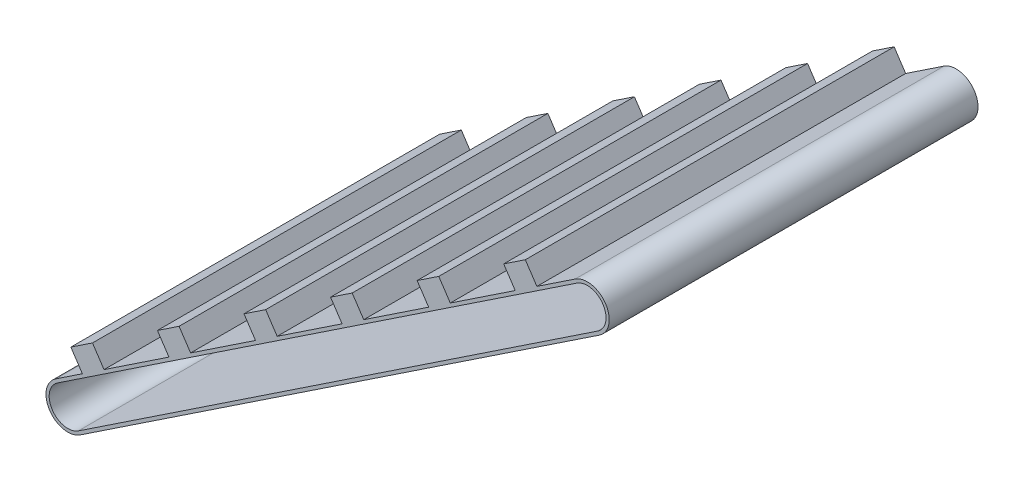
SolidWorks part; units mm, degrees
ref_plane "Front Plane" through (0, 0, 0) normal (0, 0, 1) x (1, 0, 0)
ref_plane "Top Plane" through (0, 0, 0) normal (0, 1, 0) x (1, 0, 0)
ref_plane "Right Plane" through (0, 0, 0) normal (1, 0, 0) x (0, 0, -1)
sketch "Sketch1" plane through (0, 0, 0) normal (0, 0, 1) x (1, 0, 0)
  line L0 (-1.9965, 2.9957) -> (97.8587, 69.546)
  line L1 (0, 0) -> (99.8552, 66.5503) construction
  line L2 (1.9965, -2.9957) -> (101.8517, 63.5547)
  line L3 (-2.335, 3.5035) -> (97.5202, 70.0538)
  line L4 (2.335, -3.5035) -> (102.1901, 63.0468)
  arc A0 (-1.9965, 2.9957) -> (1.9965, -2.9957) centre (0, 0) ccw
  arc A1 (101.8517, 63.5547) -> (97.8587, 69.546) centre (99.8552, 66.5503) ccw
  arc A2 (-2.335, 3.5035) -> (2.335, -3.5035) centre (0, 0) ccw
  arc A3 (102.1901, 63.0468) -> (97.5202, 70.0538) centre (99.8552, 66.5503) ccw
  dimension "D1" = 7.2
  dimension "D3" = 8.4206
  dimension "D2" = 120
extrude "Boss-Extrude1" add sketch "Sketch1" along normal blind 70.9
sketch "Sketch2" plane through (-2.335, 3.5035, 0) normal (-0.5546, 0.8321, 0) x (0.8321, 0.5546, 0)
  line L0 (120, 0) -> (0, 0) construction
  line L1 (6.1534, 0) -> (10.8742, 0)
  line L2 (6.1534, 0) -> (6.1534, -70.9)
  line L3 (6.1534, -70.9) -> (10.8742, -70.9)
  line L4 (10.8742, 0) -> (10.8742, -70.9)
  line L5 (120, -70.9) -> (0, -70.9) construction
ref_plane "Plane2" through (-2.335, 3.5035, 0) normal (-0.8321, -0.5546, 0) x (0, 0, 1)
sketch "Sketch5" plane through (-2.335, 3.5035, 0) normal (-0.5546, 0.8321, 0) x (0.8321, 0.5546, 0)
  line L0 (0, 0) -> (120, 0) construction
  line L1 (6.1534, -70.9) -> (11.1534, -70.9)
  line L2 (6.1534, -70.9) -> (6.1534, 0)
  line L3 (6.1534, 0) -> (11.1534, 0)
  line L4 (11.1534, -70.9) -> (11.1534, 0)
  dimension "D1" = 5
sketch "Sketch6" plane through (-2.335, 3.5035, 0) normal (-0.5546, 0.8321, 0) x (0.8321, 0.5546, 0)
  line L0 (120, -70.9) -> (0, -70.9) construction
  line L1 (6.1534, 0) -> (11.1534, 0)
  line L2 (6.1534, 0) -> (6.1534, -70.9)
  line L3 (6.1534, -70.9) -> (11.1534, -70.9)
  line L4 (11.1534, 0) -> (11.1534, -70.9)
  dimension "D1" = 5
extrude "Boss-Extrude2" add sketch "Sketch6" along normal blind 4
pattern_linear "LPattern1" count 6 spacing 20 along (0.8321, 0.5546, 0) of "Boss-Extrude2"
